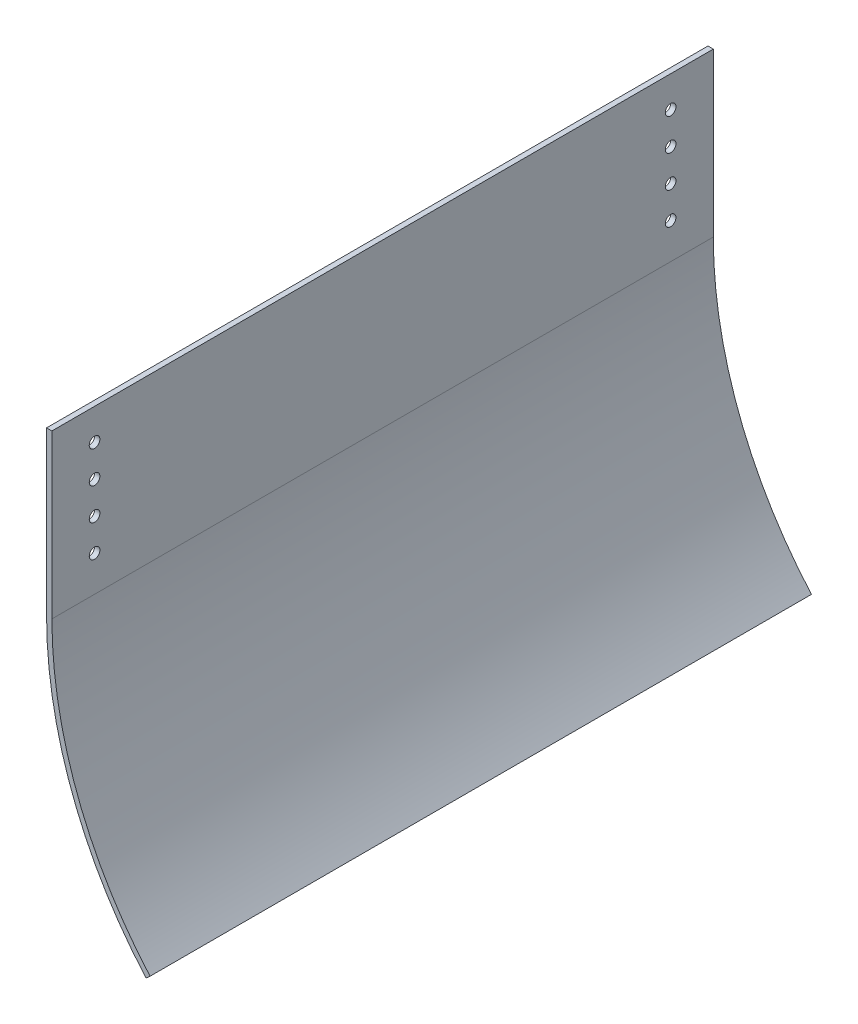
SolidWorks part; units mm, degrees
ref_plane "Front Plane" through (0, 0, 0) normal (0, 0, 1) x (1, 0, 0)
ref_plane "Top Plane" through (0, 0, 0) normal (0, 1, 0) x (1, 0, 0)
ref_plane "Right Plane" through (0, 0, 0) normal (1, 0, 0) x (0, 0, -1)
sketch "Sketch1" plane through (0, 0, 0) normal (0, 0, 1) x (1, 0, 0)
  line L2 (812.5417, 1387.3698) -> (812.5417, 1484.2708)
  line L4 (815.7167, 1387.3698) -> (815.7167, 1484.2708)
  line L5 (812.5417, 1484.2708) -> (815.7167, 1484.2708)
  line L6 (874.1429, 1232.3666) -> (871.7578, 1230.2708)
  arc A0 (812.5417, 1387.3698) -> (871.7578, 1230.2708) centre (1050.5397, 1387.3698) ccw
  arc A1 (815.7167, 1387.3698) -> (874.1429, 1232.3666) centre (1050.5397, 1387.3698) ccw
  dimension "D1" = 237.998
  dimension "D3" = 237.998
  dimension "D4" = 3.175
extrude "Boss-Extrude1" add sketch "Sketch1" along normal blind 393.7
sketch "Sketch2" plane through (815.7167, 0, 0) normal (1, 0, 0) x (0, 0, -1)
  line L1 (-393.7, 1387.3698) -> (-393.7, 1484.2708) construction
  line L2 (-393.7, 1484.2708) -> (0, 1484.2708) construction
  line L4 (0, 1387.3698) -> (0, 1484.2708) construction
  circle A0 centre (-368.3, 1446.6788) radius 3.175
  circle A1 centre (-368.3, 1427.6288) radius 3.175
  circle A2 centre (-368.3, 1408.5788) radius 3.175
  circle A3 centre (-25.4, 1465.7288) radius 3.175
  circle A4 centre (-25.4, 1446.6788) radius 3.175
  circle A5 centre (-25.4, 1427.6288) radius 3.175
  circle A6 centre (-368.3, 1465.7288) radius 3.175
  circle A7 centre (-25.4, 1408.5788) radius 3.175
  point P24 (0, 0)
  dimension "D1" = 6.35
  dimension "D2" = 6.35
  dimension "D3" = 6.35
  dimension "D11" = 6.35
  dimension "D13" = 6.35
  dimension "D14" = 6.35
  dimension "D15" = 6.35
  dimension "D16" = 6.35
  dimension "D4" = 18.542
  dimension "D5" = 19.05
  dimension "D6" = 19.05
  dimension "D7" = 25.4
  dimension "D8" = 25.4
  dimension "D9" = 25.4
  dimension "D10" = 25.4
  dimension "D12" = 19.05
  dimension "D17" = 25.4
  dimension "D18" = 25.4
  dimension "D19" = 25.4
  dimension "D20" = 25.4
  dimension "D21" = 18.542
  dimension "D22" = 19.05
  dimension "D23" = 19.05
  dimension "D24" = 19.05
extrude "Cut-Extrude1" cut sketch "Sketch2" against normal through all
